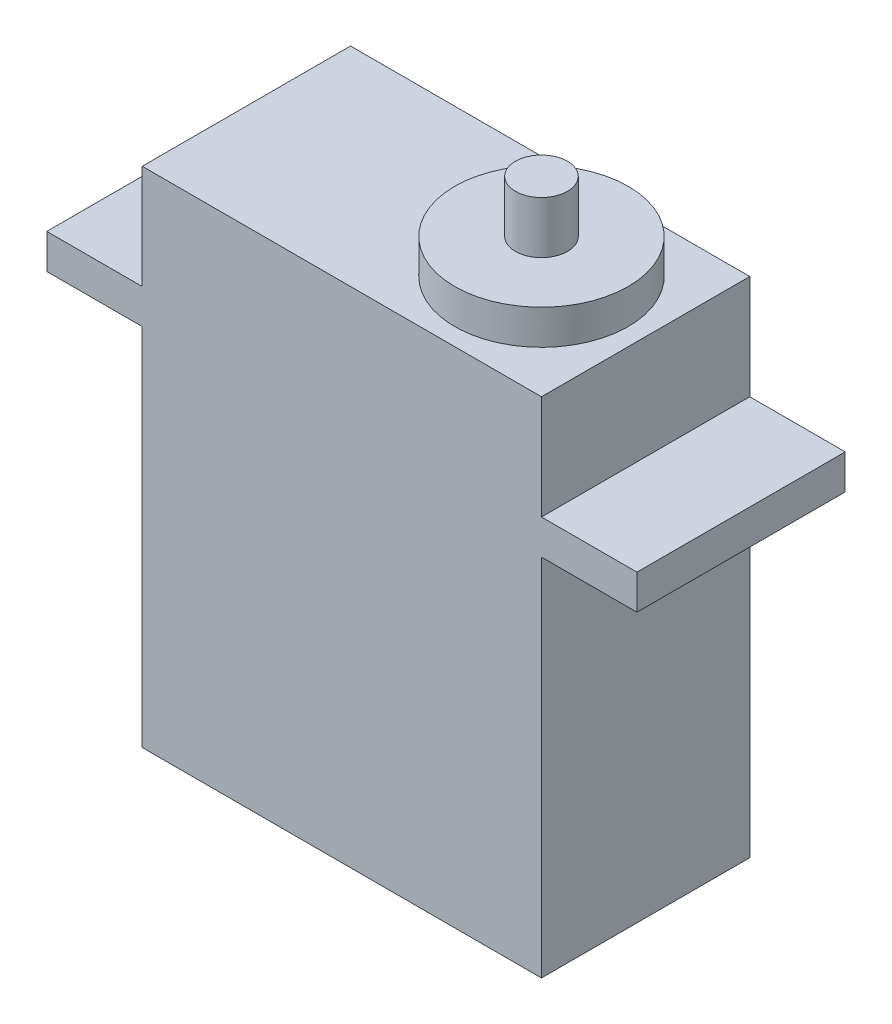
SolidWorks part; units mm, degrees
ref_plane "Front Plane" through (0, 0, 0) normal (0, 0, 1) x (1, 0, 0)
ref_plane "Top Plane" through (0, 0, 0) normal (0, 1, 0) x (1, 0, 0)
ref_plane "Right Plane" through (0, 0, 0) normal (1, 0, 0) x (0, 0, -1)
sketch "Sketch1" plane through (0, 0, 0) normal (0, 0, 1) x (1, 0, 0)
  line L1 (0, 0) -> (23, 0)
  line L2 (0, 0) -> (0, 29)
  line L3 (0, 29) -> (23, 29)
  line L4 (23, 0) -> (23, 29)
  dimension "D1" = 23
  dimension "D2" = 29
extrude "Boss-Extrude1" add sketch "Sketch1" along normal blind 12
sketch "Sketch3" plane through (0, 0, 12) normal (0, 0, 1) x (1, 0, 0)
  line L0 (0, 0) -> (23, 0) construction
  line L1 (-5.5, 21) -> (28.5, 21)
  line L2 (-5.5, 21) -> (-5.5, 23)
  line L3 (-5.5, 23) -> (28.5, 23)
  line L4 (28.5, 21) -> (28.5, 23)
  line L5 (11.5, -961) -> (11.5, 49039) construction
  line L6 (23, 29) -> (0, 29) construction
  point P7 (11.5, 23)
  point P11 (11.5, 29)
  dimension "D1" = 21
  dimension "D2" = 2
  dimension "D3" = 34
extrude "Boss-Extrude2" add sketch "Sketch3" against normal blind 12
sketch "Sketch4" plane through (0, 29, 0) normal (0, 1, 0) x (1, 0, 0)
  line L0 (-1000, -6) -> (49000, -6) construction
  line L1 (0, -12) -> (0, 0) construction
  line L2 (23, -12) -> (23, 0) construction
  circle A0 centre (17, -6) radius 5
  point P5 (0, -6)
  dimension "D1" = 10
  dimension "D2" = 6
extrude "Boss-Extrude3" add sketch "Sketch4" along normal blind 2
sketch "Sketch6" plane through (0, 31, 0) normal (0, 1, 0) x (1, 0, 0)
  circle A0 centre (17, -6) radius 1.5
  circle A1 centre (17, -6) radius 5 construction
  dimension "D1" = 3
extrude "Boss-Extrude4" add sketch "Sketch6" along normal blind 3
